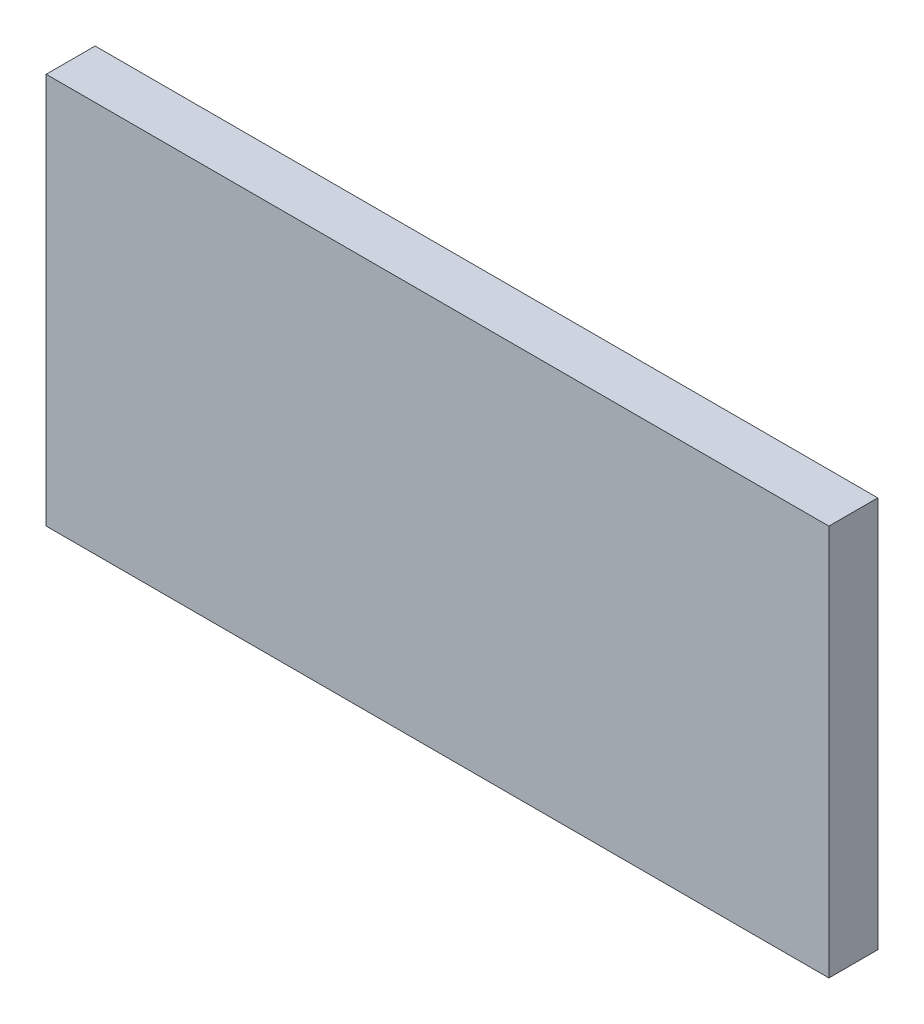
SolidWorks part; units mm, degrees
material "Cast Carbon Steel"
ref_plane "Front Plane" through (0, 0, 0) normal (0, 0, 1) x (1, 0, 0)
ref_plane "Top Plane" through (0, 0, 0) normal (0, 1, 0) x (1, 0, 0)
ref_plane "Right Plane" through (0, 0, 0) normal (1, 0, 0) x (0, 0, -1)
sketch "Sketch1" plane through (0, 0, 0) normal (0, 0, 1) x (1, 0, 0)
  line L0 (0, 87.15) -> (0, 99.85) construction
  line L1 (7.6689, 87.15) -> (-7.6689, 87.15) construction
  line L2 (-8.5264, 99.85) -> (8.5264, 99.85) construction
  line L4 (-12.7, 87.15) -> (12.7, 87.15)
  line L5 (-12.7, 87.15) -> (-12.7, 99.85)
  line L6 (-12.7, 99.85) -> (12.7, 99.85)
  line L7 (12.7, 87.15) -> (12.7, 99.85)
  line L8 (-12.7, 87.15) -> (12.7, 99.85) construction
  line L9 (-12.7, 99.85) -> (12.7, 87.15) construction
  point P6 (0, 93.5)
  dimension "D1" = 25.4
  dimension "D2" = 12.7
extrude "Boss-Extrude1" add sketch "Sketch1" along normal blind 1.5875
